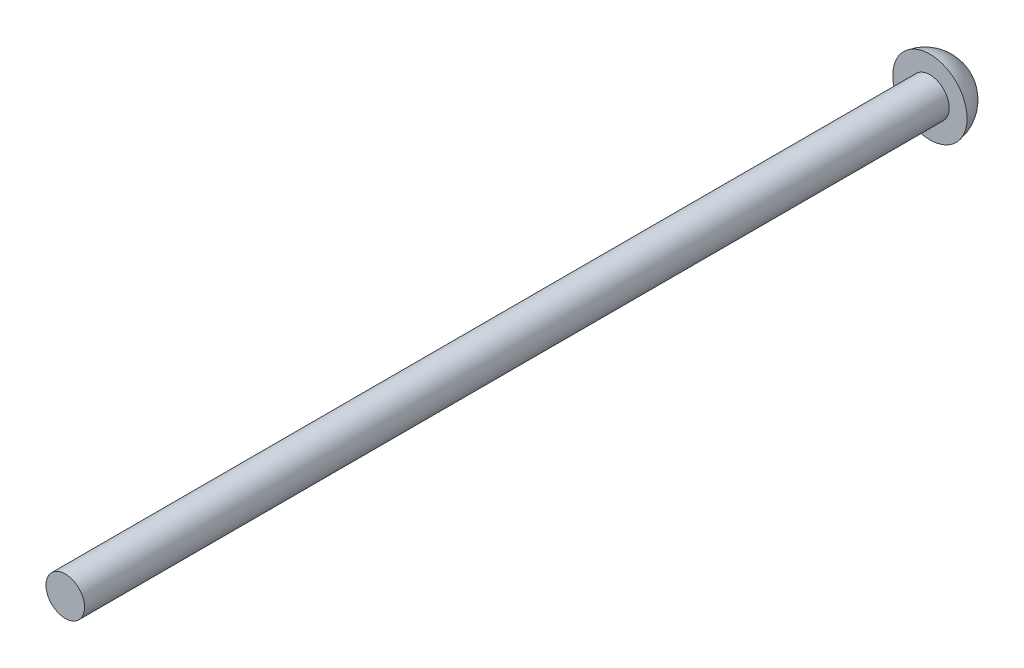
SolidWorks part; units mm, degrees
ref_plane "Front" through (0, 0, 0) normal (0, 0, 1) x (1, 0, 0)
ref_plane "Top" through (0, 0, 0) normal (0, 1, 0) x (1, 0, 0)
ref_plane "Right" through (0, 0, 0) normal (1, 0, 0) x (0, 0, -1)
sketch "Sketch1" plane through (0, 0, 0) normal (0, 1, 0) x (1, 0, 0)
  line L0 (0, 0) -> (0, 79.07)
  line L1 (0, 0) -> (1.7, 0)
  line L2 (1.7, 0) -> (1.7, 76.2)
  line L3 (1.7, 76.2) -> (3.275, 76.2)
  arc A0 (3.275, 76.2) -> (0, 79.07) centre (0, 75.7664) ccw
  dimension "D1" = 3.275
  dimension "D2" = 2.87
  dimension "D3" = 1.7
  dimension "D4" = 76.2
revolve "Revolve1" add sketch "Sketch1" angle 360 about L0
